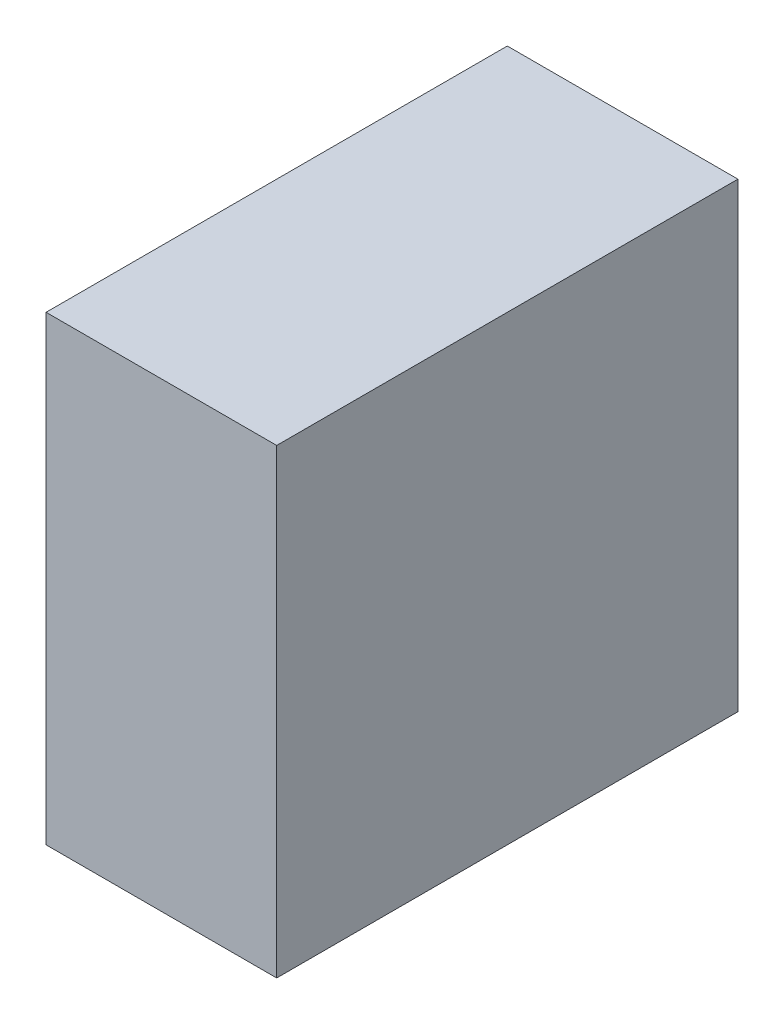
SolidWorks part; units mm, degrees
ref_plane "Piano frontale" through (0, 0, 0) normal (0, 0, 1) x (1, 0, 0)
ref_plane "Piano superiore" through (0, 0, 0) normal (0, 1, 0) x (1, 0, 0)
ref_plane "Piano destro" through (0, 0, 0) normal (1, 0, 0) x (0, 0, -1)
sketch "Schizzo1" plane through (0, 0, 0) normal (1, 0, 0) x (0, 0, -1)
  line L1 (-50, -50) -> (50, -50)
  line L2 (-50, -50) -> (-50, 50)
  line L3 (-50, 50) -> (50, 50)
  line L4 (50, -50) -> (50, 50)
  line L5 (-50, -50) -> (50, 50) construction
  line L6 (-50, 50) -> (50, -50) construction
  point P0 (0, 0)
  dimension "D1" = 100
extrude "Estrusione-Estrusione1" add sketch "Schizzo1" along normal mid plane 50 contours L2 L3 L4 L1
